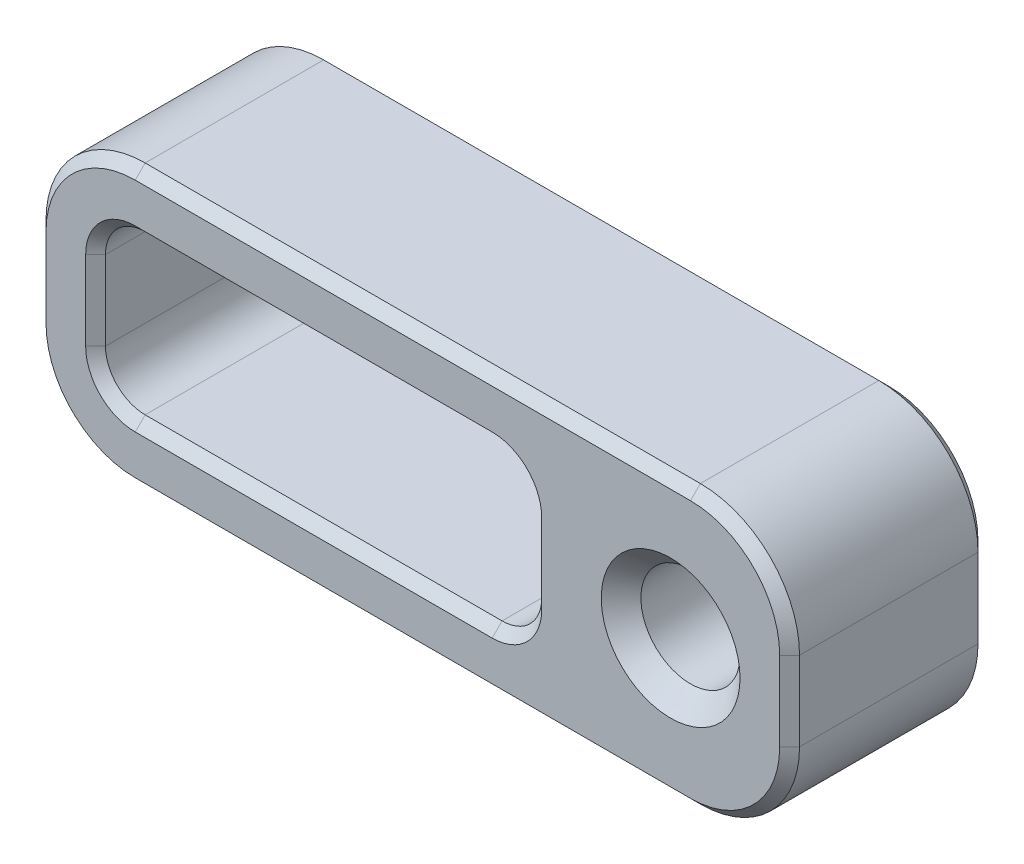
SolidWorks part; units mm, degrees
ref_plane "Front Plane" through (0, 0, 0) normal (1, 0, 0) x (0, 1, 0)
ref_plane "Top Plane" through (0, 0, 0) normal (0, 0, 1) x (0, 1, 0)
ref_plane "Right Plane" through (0, 0, 0) normal (0, 1, 0) x (-1, 0, 0)
sketch "Sketch1" plane through (0, 0, 0) normal (0, 0, 1) x (0, 1, 0)
  line L0 (2, 25) -> (6, 25)
  line L1 (2, 0) -> (6, 0)
  line L2 (0, 2) -> (0, 20)
  line L3 (2, 22) -> (6, 22)
  line L4 (8, 2) -> (8, 20)
  line L5 (11, 2) -> (11, 20)
  line L6 (2, -3) -> (6, -3)
  line L7 (-3, 2) -> (-3, 20)
  line L8 (-3, 2) -> (-3, -8)
  line L9 (2, -13) -> (6, -13)
  line L10 (11, -8) -> (11, 2)
  line L11 (4, -7) -> (2, -8) construction
  line L12 (6, -8) -> (4, -7) construction
  arc A0 (6, 0) -> (8, 2) centre (6, 2) ccw
  arc A1 (2, 0) -> (0, 2) centre (2, 2) cw
  arc A2 (0, 20) -> (2, 22) centre (2, 20) cw
  arc A3 (6, 22) -> (8, 20) centre (6, 20) cw
  arc A4 (6, 25) -> (11, 20) centre (6, 20) cw
  arc A5 (6, -3) -> (11, 2) centre (6, 2) ccw
  arc A6 (2, -3) -> (-3, 2) centre (2, 2) cw
  arc A7 (-3, 20) -> (2, 25) centre (2, 20) cw
  arc A8 (-3, -8) -> (2, -13) centre (2, -8) ccw
  arc A9 (6, -13) -> (11, -8) centre (6, -8) ccw
  circle A10 centre (4, -7) radius 2.5
  point P7 (8, 0)
  point P10 (0, 0)
  point P13 (0, 22)
  point P16 (8, 22)
  dimension "D3" = 2
  dimension "D6" = 5
  dimension "D7" = 5
  dimension "D1" = 22
  dimension "D2" = 8
  dimension "D5" = 10
  dimension "D8" = 4
  dimension "D4" = 3
extrude "Boss-Extrude1" add sketch "Sketch1" along normal blind 10 contours A7 L7 A6 L6 A5 L5 A4 L0 L3 A3 L4 A0 L1 A1 L2 A2 | L9 A9 L10 A5 L6 A6 L8 A8 A10
chamfer "Chamfer1" distance 1 angle 45 2 edges at (9.5, 4, 0) (9.5, 4, 10)
chamfer "Chamfer2" distance 0.5 angle 45 32 edges at (-6, -3, 0) (11.5355, -1.5355, 0) (-23.5355, -1.5355, 0) (13, 4, 0) (-25, 4, 0) (11.5355, 9.5355, 0) (-23.5355, 9.5355, 0) (-6, 11, 0) (-11, 8, 0) (-0.5858, 7.4142, 0) (-21.4142, 7.4142, 0) (0, 4, 0) (-22, 4, 0) (-0.5858, 0.5858, 0) (-21.4142, 0.5858, 0) (-11, 0, 0) (-6, 11, 10) (11.5355, 9.5355, 10) (-23.5355, 9.5355, 10) (13, 4, 10) (-25, 4, 10) (11.5355, -1.5355, 10) (-23.5355, -1.5355, 10) (-6, -3, 10) (-11, 8, 10) (-0.5858, 7.4142, 10) (-21.4142, 7.4142, 10) (0, 4, 10) (-22, 4, 10) (-0.5858, 0.5858, 10) (-21.4142, 0.5858, 10) (-11, 0, 10)
